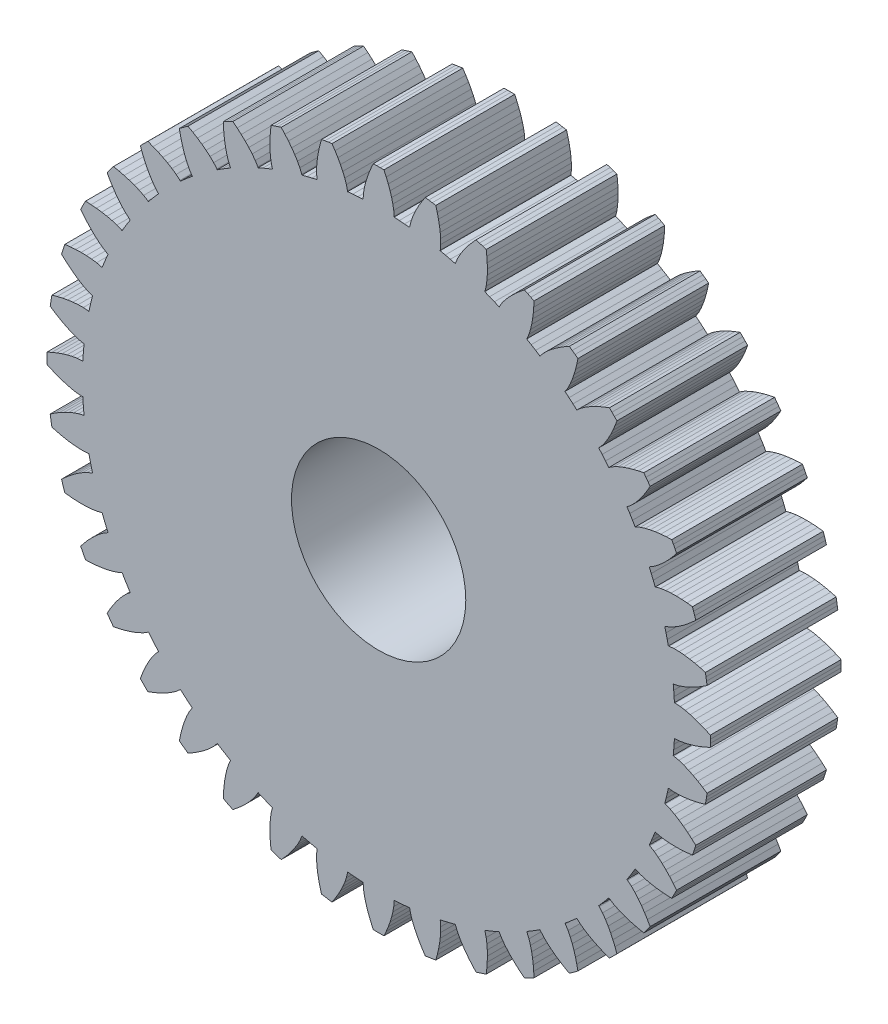
SolidWorks part; units mm, degrees
ref_plane "Спереди" through (0, 0, 0) normal (0, 0, 1) x (1, 0, 0)
ref_plane "Сверху" through (0, 0, 0) normal (0, 1, 0) x (1, 0, 0)
ref_plane "Справа" through (0, 0, 0) normal (1, 0, 0) x (0, 0, -1)
sketch "Эскиз1" plane through (0, 0, 0) normal (0, 0, 1) x (1, 0, 0)
  line L0 (27.1506, -1.416) -> (27.2141, -1.4193)
  line L1 (27.2141, -1.4193) -> (27.6733, -1.3869)
  line L2 (27.6733, -1.3869) -> (28.1347, -1.3064)
  line L3 (28.1347, -1.3064) -> (28.5972, -1.1932)
  line L4 (28.5972, -1.1932) -> (29.06, -1.0524)
  line L5 (29.06, -1.0524) -> (29.5227, -0.8869)
  line L6 (29.5227, -0.8869) -> (29.9849, -0.6985)
  line L7 (29.9849, -0.6985) -> (30.4461, -0.4885)
  line L8 (30.4461, -0.4885) -> (30.4496, -0.1628)
  line L9 (30.4496, -0.1628) -> (30.4496, 0.1628)
  line L10 (30.4496, 0.1628) -> (30.4461, 0.4885)
  line L11 (30.4461, 0.4885) -> (29.9849, 0.6985)
  line L12 (29.9849, 0.6985) -> (29.5227, 0.8869)
  line L13 (29.5227, 0.8869) -> (29.06, 1.0524)
  line L14 (29.06, 1.0524) -> (28.5972, 1.1932)
  line L15 (28.5972, 1.1932) -> (28.1347, 1.3064)
  line L16 (28.1347, 1.3064) -> (27.6733, 1.3869)
  line L17 (27.6733, 1.3869) -> (27.2141, 1.4193)
  line L18 (27.2141, 1.4193) -> (27.1506, 1.416)
  line L19 (27.1506, 1.416) -> (27.1214, 1.8942)
  line L20 (27.1214, 1.8942) -> (27.0838, 2.3718)
  line L21 (27.0838, 2.3718) -> (27.0378, 2.8488)
  line L22 (27.0378, 2.8488) -> (27.1011, 2.8554)
  line L23 (27.1011, 2.8554) -> (27.5496, 2.9593)
  line L24 (27.5496, 2.9593) -> (27.9927, 3.1109)
  line L25 (27.9927, 3.1109) -> (28.4317, 3.2951)
  line L26 (28.4317, 3.2951) -> (28.8668, 3.5065)
  line L27 (28.8668, 3.5065) -> (29.298, 3.7424)
  line L28 (29.298, 3.7424) -> (29.725, 4.0008)
  line L29 (29.725, 4.0008) -> (30.1477, 4.2804)
  line L30 (30.1477, 4.2804) -> (30.1002, 4.6025)
  line L31 (30.1002, 4.6025) -> (30.0492, 4.9242)
  line L32 (30.0492, 4.9242) -> (29.9948, 5.2453)
  line L33 (29.9948, 5.2453) -> (29.5064, 5.3805)
  line L34 (29.5064, 5.3805) -> (29.0205, 5.4943)
  line L35 (29.0205, 5.4943) -> (28.5376, 5.5854)
  line L36 (28.5376, 5.5854) -> (28.0584, 5.6521)
  line L37 (28.0584, 5.6521) -> (27.584, 5.6915)
  line L38 (27.584, 5.6915) -> (27.1157, 5.6988)
  line L39 (27.1157, 5.6988) -> (26.657, 5.659)
  line L40 (26.657, 5.659) -> (26.5948, 5.6458)
  line L41 (26.5948, 5.6458) -> (26.4912, 6.1136)
  line L42 (26.4912, 6.1136) -> (26.3794, 6.5795)
  line L43 (26.3794, 6.5795) -> (26.2593, 7.0433)
  line L44 (26.2593, 7.0433) -> (26.3207, 7.0598)
  line L45 (26.3207, 7.0598) -> (26.7475, 7.2326)
  line L46 (26.7475, 7.2326) -> (27.1614, 7.4517)
  line L47 (27.1614, 7.4517) -> (27.5662, 7.7022)
  line L48 (27.5662, 7.7022) -> (27.9629, 7.9791)
  line L49 (27.9629, 7.9791) -> (28.3518, 8.2795)
  line L50 (28.3518, 8.2795) -> (28.7332, 8.6015)
  line L51 (28.7332, 8.6015) -> (29.1069, 8.9438)
  line L52 (29.1069, 8.9438) -> (29.0096, 9.2546)
  line L53 (29.0096, 9.2546) -> (28.9089, 9.5643)
  line L54 (28.9089, 9.5643) -> (28.805, 9.8729)
  line L55 (28.805, 9.8729) -> (28.3015, 9.9301)
  line L56 (28.3015, 9.9301) -> (27.8037, 9.9665)
  line L57 (27.8037, 9.9665) -> (27.3125, 9.9809)
  line L58 (27.3125, 9.9809) -> (26.8288, 9.9718)
  line L59 (26.8288, 9.9718) -> (26.354, 9.9366)
  line L60 (26.354, 9.9366) -> (25.8904, 9.8705)
  line L61 (25.8904, 9.8705) -> (25.4436, 9.7594)
  line L62 (25.4436, 9.7594) -> (25.3842, 9.7367)
  line L63 (25.3842, 9.7367) -> (25.2087, 10.1825)
  line L64 (25.2087, 10.1825) -> (25.0253, 10.6251)
  line L65 (25.0253, 10.6251) -> (24.8342, 11.0645)
  line L66 (24.8342, 11.0645) -> (24.8923, 11.0904)
  line L67 (24.8923, 11.0904) -> (25.2867, 11.3277)
  line L68 (25.2867, 11.3277) -> (25.6613, 11.6089)
  line L69 (25.6613, 11.6089) -> (26.022, 11.9197)
  line L70 (26.022, 11.9197) -> (26.3704, 12.2553)
  line L71 (26.3704, 12.2553) -> (26.7076, 12.6128)
  line L72 (26.7076, 12.6128) -> (27.0338, 12.9905)
  line L73 (27.0338, 12.9905) -> (27.3494, 13.387)
  line L74 (27.3494, 13.387) -> (27.2047, 13.6787)
  line L75 (27.2047, 13.6787) -> (27.0568, 13.9689)
  line L76 (27.0568, 13.9689) -> (26.9059, 14.2575)
  line L77 (26.9059, 14.2575) -> (26.3996, 14.2352)
  line L78 (26.3996, 14.2352) -> (25.9023, 14.1932)
  line L79 (25.9023, 14.1932) -> (25.4149, 14.1307)
  line L80 (25.4149, 14.1307) -> (24.9386, 14.046)
  line L81 (24.9386, 14.046) -> (24.4752, 13.9369)
  line L82 (24.4752, 13.9369) -> (24.0275, 13.7991)
  line L83 (24.0275, 13.7991) -> (23.6036, 13.6195)
  line L84 (23.6036, 13.6195) -> (23.5485, 13.5878)
  line L85 (23.5485, 13.5878) -> (23.3054, 14.0006)
  line L86 (23.3054, 14.0006) -> (23.0551, 14.4091)
  line L87 (23.0551, 14.4091) -> (22.7976, 14.8132)
  line L88 (22.7976, 14.8132) -> (22.8509, 14.8478)
  line L89 (22.8509, 14.8478) -> (23.2034, 15.144)
  line L90 (23.2034, 15.144) -> (23.5294, 15.4803)
  line L91 (23.5294, 15.4803) -> (23.8369, 15.8437)
  line L92 (23.8369, 15.8437) -> (24.1286, 16.2296)
  line L93 (24.1286, 16.2296) -> (24.4057, 16.6355)
  line L94 (24.4057, 16.6355) -> (24.6688, 17.0596)
  line L95 (24.6688, 17.0596) -> (24.9185, 17.5006)
  line L96 (24.9185, 17.5006) -> (24.7299, 17.7661)
  line L97 (24.7299, 17.7661) -> (24.5385, 18.0295)
  line L98 (24.5385, 18.0295) -> (24.3443, 18.2909)
  line L99 (24.3443, 18.2909) -> (23.8477, 18.1897)
  line L100 (23.8477, 18.1897) -> (23.3631, 18.0705)
  line L101 (23.3631, 18.0705) -> (22.8914, 17.9324)
  line L102 (22.8914, 17.9324) -> (22.4343, 17.7743)
  line L103 (22.4343, 17.7743) -> (21.9936, 17.5941)
  line L104 (21.9936, 17.5941) -> (21.573, 17.388)
  line L105 (21.573, 17.388) -> (21.1824, 17.1443)
  line L106 (21.1824, 17.1443) -> (21.133, 17.1043)
  line L107 (21.133, 17.1043) -> (20.8283, 17.474)
  line L108 (20.8283, 17.474) -> (20.5172, 17.8383)
  line L109 (20.5172, 17.8383) -> (20.1996, 18.1971)
  line L110 (20.1996, 18.1971) -> (20.2469, 18.2397)
  line L111 (20.2469, 18.2397) -> (20.5487, 18.5874)
  line L112 (20.5487, 18.5874) -> (20.818, 18.9705)
  line L113 (20.818, 18.9705) -> (21.065, 19.3775)
  line L114 (21.065, 19.3775) -> (21.2927, 19.8044)
  line L115 (21.2927, 19.8044) -> (21.5028, 20.2486)
  line L116 (21.5028, 20.2486) -> (21.6964, 20.7086)
  line L117 (21.6964, 20.7086) -> (21.874, 21.1832)
  line L118 (21.874, 21.1832) -> (21.6462, 21.416)
  line L119 (21.6462, 21.416) -> (21.416, 21.6462)
  line L120 (21.416, 21.6462) -> (21.1832, 21.874)
  line L121 (21.1832, 21.874) -> (20.7086, 21.6964)
  line L122 (20.7086, 21.6964) -> (20.2486, 21.5028)
  line L123 (20.2486, 21.5028) -> (19.8044, 21.2927)
  line L124 (19.8044, 21.2927) -> (19.3775, 21.065)
  line L125 (19.3775, 21.065) -> (18.9705, 20.818)
  line L126 (18.9705, 20.818) -> (18.5874, 20.5487)
  line L127 (18.5874, 20.5487) -> (18.2397, 20.2469)
  line L128 (18.2397, 20.2469) -> (18.1971, 20.1996)
  line L129 (18.1971, 20.1996) -> (17.8383, 20.5172)
  line L130 (17.8383, 20.5172) -> (17.474, 20.8283)
  line L131 (17.474, 20.8283) -> (17.1043, 21.133)
  line L132 (17.1043, 21.133) -> (17.1443, 21.1824)
  line L133 (17.1443, 21.1824) -> (17.388, 21.573)
  line L134 (17.388, 21.573) -> (17.5941, 21.9936)
  line L135 (17.5941, 21.9936) -> (17.7743, 22.4343)
  line L136 (17.7743, 22.4343) -> (17.9324, 22.8914)
  line L137 (17.9324, 22.8914) -> (18.0705, 23.3631)
  line L138 (18.0705, 23.3631) -> (18.1897, 23.8477)
  line L139 (18.1897, 23.8477) -> (18.2909, 24.3443)
  line L140 (18.2909, 24.3443) -> (18.0295, 24.5385)
  line L141 (18.0295, 24.5385) -> (17.7661, 24.7299)
  line L142 (17.7661, 24.7299) -> (17.5006, 24.9185)
  line L143 (17.5006, 24.9185) -> (17.0596, 24.6688)
  line L144 (17.0596, 24.6688) -> (16.6355, 24.4057)
  line L145 (16.6355, 24.4057) -> (16.2296, 24.1286)
  line L146 (16.2296, 24.1286) -> (15.8437, 23.8369)
  line L147 (15.8437, 23.8369) -> (15.4803, 23.5294)
  line L148 (15.4803, 23.5294) -> (15.144, 23.2034)
  line L149 (15.144, 23.2034) -> (14.8478, 22.8509)
  line L150 (14.8478, 22.8509) -> (14.8132, 22.7976)
  line L151 (14.8132, 22.7976) -> (14.4091, 23.0551)
  line L152 (14.4091, 23.0551) -> (14.0006, 23.3054)
  line L153 (14.0006, 23.3054) -> (13.5878, 23.5485)
  line L154 (13.5878, 23.5485) -> (13.6195, 23.6036)
  line L155 (13.6195, 23.6036) -> (13.7991, 24.0275)
  line L156 (13.7991, 24.0275) -> (13.9369, 24.4752)
  line L157 (13.9369, 24.4752) -> (14.046, 24.9386)
  line L158 (14.046, 24.9386) -> (14.1307, 25.4149)
  line L159 (14.1307, 25.4149) -> (14.1932, 25.9023)
  line L160 (14.1932, 25.9023) -> (14.2352, 26.3996)
  line L161 (14.2352, 26.3996) -> (14.2575, 26.9059)
  line L162 (14.2575, 26.9059) -> (13.9689, 27.0568)
  line L163 (13.9689, 27.0568) -> (13.6787, 27.2047)
  line L164 (13.6787, 27.2047) -> (13.387, 27.3494)
  line L165 (13.387, 27.3494) -> (12.9905, 27.0338)
  line L166 (12.9905, 27.0338) -> (12.6128, 26.7076)
  line L167 (12.6128, 26.7076) -> (12.2553, 26.3704)
  line L168 (12.2553, 26.3704) -> (11.9197, 26.022)
  line L169 (11.9197, 26.022) -> (11.6089, 25.6613)
  line L170 (11.6089, 25.6613) -> (11.3277, 25.2867)
  line L171 (11.3277, 25.2867) -> (11.0904, 24.8923)
  line L172 (11.0904, 24.8923) -> (11.0645, 24.8342)
  line L173 (11.0645, 24.8342) -> (10.6251, 25.0253)
  line L174 (10.6251, 25.0253) -> (10.1825, 25.2087)
  line L175 (10.1825, 25.2087) -> (9.7367, 25.3842)
  line L176 (9.7367, 25.3842) -> (9.7594, 25.4436)
  line L177 (9.7594, 25.4436) -> (9.8705, 25.8904)
  line L178 (9.8705, 25.8904) -> (9.9366, 26.354)
  line L179 (9.9366, 26.354) -> (9.9718, 26.8288)
  line L180 (9.9718, 26.8288) -> (9.9809, 27.3125)
  line L181 (9.9809, 27.3125) -> (9.9665, 27.8037)
  line L182 (9.9665, 27.8037) -> (9.9301, 28.3015)
  line L183 (9.9301, 28.3015) -> (9.8729, 28.805)
  line L184 (9.8729, 28.805) -> (9.5643, 28.9089)
  line L185 (9.5643, 28.9089) -> (9.2546, 29.0096)
  line L186 (9.2546, 29.0096) -> (8.9438, 29.1069)
  line L187 (8.9438, 29.1069) -> (8.6015, 28.7332)
  line L188 (8.6015, 28.7332) -> (8.2795, 28.3518)
  line L189 (8.2795, 28.3518) -> (7.9791, 27.9629)
  line L190 (7.9791, 27.9629) -> (7.7022, 27.5662)
  line L191 (7.7022, 27.5662) -> (7.4517, 27.1614)
  line L192 (7.4517, 27.1614) -> (7.2326, 26.7475)
  line L193 (7.2326, 26.7475) -> (7.0598, 26.3207)
  line L194 (7.0598, 26.3207) -> (7.0433, 26.2593)
  line L195 (7.0433, 26.2593) -> (6.5795, 26.3794)
  line L196 (6.5795, 26.3794) -> (6.1136, 26.4912)
  line L197 (6.1136, 26.4912) -> (5.6458, 26.5948)
  line L198 (5.6458, 26.5948) -> (5.659, 26.657)
  line L199 (5.659, 26.657) -> (5.6988, 27.1157)
  line L200 (5.6988, 27.1157) -> (5.6915, 27.584)
  line L201 (5.6915, 27.584) -> (5.6521, 28.0584)
  line L202 (5.6521, 28.0584) -> (5.5854, 28.5376)
  line L203 (5.5854, 28.5376) -> (5.4943, 29.0205)
  line L204 (5.4943, 29.0205) -> (5.3805, 29.5064)
  line L205 (5.3805, 29.5064) -> (5.2453, 29.9948)
  line L206 (5.2453, 29.9948) -> (4.9242, 30.0492)
  line L207 (4.9242, 30.0492) -> (4.6025, 30.1002)
  line L208 (4.6025, 30.1002) -> (4.2804, 30.1477)
  line L209 (4.2804, 30.1477) -> (4.0008, 29.725)
  line L210 (4.0008, 29.725) -> (3.7424, 29.298)
  line L211 (3.7424, 29.298) -> (3.5065, 28.8668)
  line L212 (3.5065, 28.8668) -> (3.2951, 28.4317)
  line L213 (3.2951, 28.4317) -> (3.1109, 27.9927)
  line L214 (3.1109, 27.9927) -> (2.9593, 27.5496)
  line L215 (2.9593, 27.5496) -> (2.8554, 27.1011)
  line L216 (2.8554, 27.1011) -> (2.8488, 27.0378)
  line L217 (2.8488, 27.0378) -> (2.3718, 27.0838)
  line L218 (2.3718, 27.0838) -> (1.8942, 27.1214)
  line L219 (1.8942, 27.1214) -> (1.416, 27.1506)
  line L220 (1.416, 27.1506) -> (1.4193, 27.2141)
  line L221 (1.4193, 27.2141) -> (1.3869, 27.6733)
  line L222 (1.3869, 27.6733) -> (1.3064, 28.1347)
  line L223 (1.3064, 28.1347) -> (1.1932, 28.5972)
  line L224 (1.1932, 28.5972) -> (1.0524, 29.06)
  line L225 (1.0524, 29.06) -> (0.8869, 29.5227)
  line L226 (0.8869, 29.5227) -> (0.6985, 29.9849)
  line L227 (0.6985, 29.9849) -> (0.4885, 30.4461)
  line L228 (0.4885, 30.4461) -> (0.1628, 30.4496)
  line L229 (0.1628, 30.4496) -> (-0.1628, 30.4496)
  line L230 (-0.1628, 30.4496) -> (-0.4885, 30.4461)
  line L231 (-0.4885, 30.4461) -> (-0.6985, 29.9849)
  line L232 (-0.6985, 29.9849) -> (-0.8869, 29.5227)
  line L233 (-0.8869, 29.5227) -> (-1.0524, 29.06)
  line L234 (-1.0524, 29.06) -> (-1.1932, 28.5972)
  line L235 (-1.1932, 28.5972) -> (-1.3064, 28.1347)
  line L236 (-1.3064, 28.1347) -> (-1.3869, 27.6733)
  line L237 (-1.3869, 27.6733) -> (-1.4193, 27.2141)
  line L238 (-1.4193, 27.2141) -> (-1.416, 27.1506)
  line L239 (-1.416, 27.1506) -> (-1.8942, 27.1214)
  line L240 (-1.8942, 27.1214) -> (-2.3718, 27.0838)
  line L241 (-2.3718, 27.0838) -> (-2.8488, 27.0378)
  line L242 (-2.8488, 27.0378) -> (-2.8554, 27.1011)
  line L243 (-2.8554, 27.1011) -> (-2.9593, 27.5496)
  line L244 (-2.9593, 27.5496) -> (-3.1109, 27.9927)
  line L245 (-3.1109, 27.9927) -> (-3.2951, 28.4317)
  line L246 (-3.2951, 28.4317) -> (-3.5065, 28.8668)
  line L247 (-3.5065, 28.8668) -> (-3.7424, 29.298)
  line L248 (-3.7424, 29.298) -> (-4.0008, 29.725)
  line L249 (-4.0008, 29.725) -> (-4.2804, 30.1477)
  line L250 (-4.2804, 30.1477) -> (-4.6025, 30.1002)
  line L251 (-4.6025, 30.1002) -> (-4.9242, 30.0492)
  line L252 (-4.9242, 30.0492) -> (-5.2453, 29.9948)
  line L253 (-5.2453, 29.9948) -> (-5.3805, 29.5064)
  line L254 (-5.3805, 29.5064) -> (-5.4943, 29.0205)
  line L255 (-5.4943, 29.0205) -> (-5.5854, 28.5376)
  line L256 (-5.5854, 28.5376) -> (-5.6521, 28.0584)
  line L257 (-5.6521, 28.0584) -> (-5.6915, 27.584)
  line L258 (-5.6915, 27.584) -> (-5.6988, 27.1157)
  line L259 (-5.6988, 27.1157) -> (-5.659, 26.657)
  line L260 (-5.659, 26.657) -> (-5.6458, 26.5948)
  line L261 (-5.6458, 26.5948) -> (-6.1136, 26.4912)
  line L262 (-6.1136, 26.4912) -> (-6.5795, 26.3794)
  line L263 (-6.5795, 26.3794) -> (-7.0433, 26.2593)
  line L264 (-7.0433, 26.2593) -> (-7.0598, 26.3207)
  line L265 (-7.0598, 26.3207) -> (-7.2326, 26.7475)
  line L266 (-7.2326, 26.7475) -> (-7.4517, 27.1614)
  line L267 (-7.4517, 27.1614) -> (-7.7022, 27.5662)
  line L268 (-7.7022, 27.5662) -> (-7.9791, 27.9629)
  line L269 (-7.9791, 27.9629) -> (-8.2795, 28.3518)
  line L270 (-8.2795, 28.3518) -> (-8.6015, 28.7332)
  line L271 (-8.6015, 28.7332) -> (-8.9438, 29.1069)
  line L272 (-8.9438, 29.1069) -> (-9.2546, 29.0096)
  line L273 (-9.2546, 29.0096) -> (-9.5643, 28.9089)
  line L274 (-9.5643, 28.9089) -> (-9.8729, 28.805)
  line L275 (-9.8729, 28.805) -> (-9.9301, 28.3015)
  line L276 (-9.9301, 28.3015) -> (-9.9665, 27.8037)
  line L277 (-9.9665, 27.8037) -> (-9.9809, 27.3125)
  line L278 (-9.9809, 27.3125) -> (-9.9718, 26.8288)
  line L279 (-9.9718, 26.8288) -> (-9.9366, 26.354)
  line L280 (-9.9366, 26.354) -> (-9.8705, 25.8904)
  line L281 (-9.8705, 25.8904) -> (-9.7594, 25.4436)
  line L282 (-9.7594, 25.4436) -> (-9.7367, 25.3842)
  line L283 (-9.7367, 25.3842) -> (-10.1825, 25.2087)
  line L284 (-10.1825, 25.2087) -> (-10.6251, 25.0253)
  line L285 (-10.6251, 25.0253) -> (-11.0645, 24.8342)
  line L286 (-11.0645, 24.8342) -> (-11.0904, 24.8923)
  line L287 (-11.0904, 24.8923) -> (-11.3277, 25.2867)
  line L288 (-11.3277, 25.2867) -> (-11.6089, 25.6613)
  line L289 (-11.6089, 25.6613) -> (-11.9197, 26.022)
  line L290 (-11.9197, 26.022) -> (-12.2553, 26.3704)
  line L291 (-12.2553, 26.3704) -> (-12.6128, 26.7076)
  line L292 (-12.6128, 26.7076) -> (-12.9905, 27.0338)
  line L293 (-12.9905, 27.0338) -> (-13.387, 27.3494)
  line L294 (-13.387, 27.3494) -> (-13.6787, 27.2047)
  line L295 (-13.6787, 27.2047) -> (-13.9689, 27.0568)
  line L296 (-13.9689, 27.0568) -> (-14.2575, 26.9059)
  line L297 (-14.2575, 26.9059) -> (-14.2352, 26.3996)
  line L298 (-14.2352, 26.3996) -> (-14.1932, 25.9023)
  line L299 (-14.1932, 25.9023) -> (-14.1307, 25.4149)
  line L300 (-14.1307, 25.4149) -> (-14.046, 24.9386)
  line L301 (-14.046, 24.9386) -> (-13.9369, 24.4752)
  line L302 (-13.9369, 24.4752) -> (-13.7991, 24.0275)
  line L303 (-13.7991, 24.0275) -> (-13.6195, 23.6036)
  line L304 (-13.6195, 23.6036) -> (-13.5878, 23.5485)
  line L305 (-13.5878, 23.5485) -> (-14.0006, 23.3054)
  line L306 (-14.0006, 23.3054) -> (-14.4091, 23.0551)
  line L307 (-14.4091, 23.0551) -> (-14.8132, 22.7976)
  line L308 (-14.8132, 22.7976) -> (-14.8478, 22.8509)
  line L309 (-14.8478, 22.8509) -> (-15.144, 23.2034)
  line L310 (-15.144, 23.2034) -> (-15.4803, 23.5294)
  line L311 (-15.4803, 23.5294) -> (-15.8437, 23.8369)
  line L312 (-15.8437, 23.8369) -> (-16.2296, 24.1286)
  line L313 (-16.2296, 24.1286) -> (-16.6355, 24.4057)
  line L314 (-16.6355, 24.4057) -> (-17.0596, 24.6688)
  line L315 (-17.0596, 24.6688) -> (-17.5006, 24.9185)
  line L316 (-17.5006, 24.9185) -> (-17.7661, 24.7299)
  line L317 (-17.7661, 24.7299) -> (-18.0295, 24.5385)
  line L318 (-18.0295, 24.5385) -> (-18.2909, 24.3443)
  line L319 (-18.2909, 24.3443) -> (-18.1897, 23.8477)
  line L320 (-18.1897, 23.8477) -> (-18.0705, 23.3631)
  line L321 (-18.0705, 23.3631) -> (-17.9324, 22.8914)
  line L322 (-17.9324, 22.8914) -> (-17.7743, 22.4343)
  line L323 (-17.7743, 22.4343) -> (-17.5941, 21.9936)
  line L324 (-17.5941, 21.9936) -> (-17.388, 21.573)
  line L325 (-17.388, 21.573) -> (-17.1443, 21.1824)
  line L326 (-17.1443, 21.1824) -> (-17.1043, 21.133)
  line L327 (-17.1043, 21.133) -> (-17.474, 20.8283)
  line L328 (-17.474, 20.8283) -> (-17.8383, 20.5172)
  line L329 (-17.8383, 20.5172) -> (-18.1971, 20.1996)
  line L330 (-18.1971, 20.1996) -> (-18.2397, 20.2469)
  line L331 (-18.2397, 20.2469) -> (-18.5874, 20.5487)
  line L332 (-18.5874, 20.5487) -> (-18.9705, 20.818)
  line L333 (-18.9705, 20.818) -> (-19.3775, 21.065)
  line L334 (-19.3775, 21.065) -> (-19.8044, 21.2927)
  line L335 (-19.8044, 21.2927) -> (-20.2486, 21.5028)
  line L336 (-20.2486, 21.5028) -> (-20.7086, 21.6964)
  line L337 (-20.7086, 21.6964) -> (-21.1832, 21.874)
  line L338 (-21.1832, 21.874) -> (-21.416, 21.6462)
  line L339 (-21.416, 21.6462) -> (-21.6462, 21.416)
  line L340 (-21.6462, 21.416) -> (-21.874, 21.1832)
  line L341 (-21.874, 21.1832) -> (-21.6964, 20.7086)
  line L342 (-21.6964, 20.7086) -> (-21.5028, 20.2486)
  line L343 (-21.5028, 20.2486) -> (-21.2927, 19.8044)
  line L344 (-21.2927, 19.8044) -> (-21.065, 19.3775)
  line L345 (-21.065, 19.3775) -> (-20.818, 18.9705)
  line L346 (-20.818, 18.9705) -> (-20.5487, 18.5874)
  line L347 (-20.5487, 18.5874) -> (-20.2469, 18.2397)
  line L348 (-20.2469, 18.2397) -> (-20.1996, 18.1971)
  line L349 (-20.1996, 18.1971) -> (-20.5172, 17.8383)
  line L350 (-20.5172, 17.8383) -> (-20.8283, 17.474)
  line L351 (-20.8283, 17.474) -> (-21.133, 17.1043)
  line L352 (-21.133, 17.1043) -> (-21.1824, 17.1443)
  line L353 (-21.1824, 17.1443) -> (-21.573, 17.388)
  line L354 (-21.573, 17.388) -> (-21.9936, 17.5941)
  line L355 (-21.9936, 17.5941) -> (-22.4343, 17.7743)
  line L356 (-22.4343, 17.7743) -> (-22.8914, 17.9324)
  line L357 (-22.8914, 17.9324) -> (-23.3631, 18.0705)
  line L358 (-23.3631, 18.0705) -> (-23.8477, 18.1897)
  line L359 (-23.8477, 18.1897) -> (-24.3443, 18.2909)
  line L360 (-24.3443, 18.2909) -> (-24.5385, 18.0295)
  line L361 (-24.5385, 18.0295) -> (-24.7299, 17.7661)
  line L362 (-24.7299, 17.7661) -> (-24.9185, 17.5006)
  line L363 (-24.9185, 17.5006) -> (-24.6688, 17.0596)
  line L364 (-24.6688, 17.0596) -> (-24.4057, 16.6355)
  line L365 (-24.4057, 16.6355) -> (-24.1286, 16.2296)
  line L366 (-24.1286, 16.2296) -> (-23.8369, 15.8437)
  line L367 (-23.8369, 15.8437) -> (-23.5294, 15.4803)
  line L368 (-23.5294, 15.4803) -> (-23.2034, 15.144)
  line L369 (-23.2034, 15.144) -> (-22.8509, 14.8478)
  line L370 (-22.8509, 14.8478) -> (-22.7976, 14.8132)
  line L371 (-22.7976, 14.8132) -> (-23.0551, 14.4091)
  line L372 (-23.0551, 14.4091) -> (-23.3054, 14.0006)
  line L373 (-23.3054, 14.0006) -> (-23.5485, 13.5878)
  line L374 (-23.5485, 13.5878) -> (-23.6036, 13.6195)
  line L375 (-23.6036, 13.6195) -> (-24.0275, 13.7991)
  line L376 (-24.0275, 13.7991) -> (-24.4752, 13.9369)
  line L377 (-24.4752, 13.9369) -> (-24.9386, 14.046)
  line L378 (-24.9386, 14.046) -> (-25.4149, 14.1307)
  line L379 (-25.4149, 14.1307) -> (-25.9023, 14.1932)
  line L380 (-25.9023, 14.1932) -> (-26.3996, 14.2352)
  line L381 (-26.3996, 14.2352) -> (-26.9059, 14.2575)
  line L382 (-26.9059, 14.2575) -> (-27.0568, 13.9689)
  line L383 (-27.0568, 13.9689) -> (-27.2047, 13.6787)
  line L384 (-27.2047, 13.6787) -> (-27.3494, 13.387)
  line L385 (-27.3494, 13.387) -> (-27.0338, 12.9905)
  line L386 (-27.0338, 12.9905) -> (-26.7076, 12.6128)
  line L387 (-26.7076, 12.6128) -> (-26.3704, 12.2553)
  line L388 (-26.3704, 12.2553) -> (-26.022, 11.9197)
  line L389 (-26.022, 11.9197) -> (-25.6613, 11.6089)
  line L390 (-25.6613, 11.6089) -> (-25.2867, 11.3277)
  line L391 (-25.2867, 11.3277) -> (-24.8923, 11.0904)
  line L392 (-24.8923, 11.0904) -> (-24.8342, 11.0645)
  line L393 (-24.8342, 11.0645) -> (-25.0253, 10.6251)
  line L394 (-25.0253, 10.6251) -> (-25.2087, 10.1825)
  line L395 (-25.2087, 10.1825) -> (-25.3842, 9.7367)
  line L396 (-25.3842, 9.7367) -> (-25.4436, 9.7594)
  line L397 (-25.4436, 9.7594) -> (-25.8904, 9.8705)
  line L398 (-25.8904, 9.8705) -> (-26.354, 9.9366)
  line L399 (-26.354, 9.9366) -> (-26.8288, 9.9718)
  line L400 (-26.8288, 9.9718) -> (-27.3125, 9.9809)
  line L401 (-27.3125, 9.9809) -> (-27.8037, 9.9665)
  line L402 (-27.8037, 9.9665) -> (-28.3015, 9.9301)
  line L403 (-28.3015, 9.9301) -> (-28.805, 9.8729)
  line L404 (-28.805, 9.8729) -> (-28.9089, 9.5643)
  line L405 (-28.9089, 9.5643) -> (-29.0096, 9.2546)
  line L406 (-29.0096, 9.2546) -> (-29.1069, 8.9438)
  line L407 (-29.1069, 8.9438) -> (-28.7332, 8.6015)
  line L408 (-28.7332, 8.6015) -> (-28.3518, 8.2795)
  line L409 (-28.3518, 8.2795) -> (-27.9629, 7.9791)
  line L410 (-27.9629, 7.9791) -> (-27.5662, 7.7022)
  line L411 (-27.5662, 7.7022) -> (-27.1614, 7.4517)
  line L412 (-27.1614, 7.4517) -> (-26.7475, 7.2326)
  line L413 (-26.7475, 7.2326) -> (-26.3207, 7.0598)
  line L414 (-26.3207, 7.0598) -> (-26.2593, 7.0433)
  line L415 (-26.2593, 7.0433) -> (-26.3794, 6.5795)
  line L416 (-26.3794, 6.5795) -> (-26.4912, 6.1136)
  line L417 (-26.4912, 6.1136) -> (-26.5948, 5.6458)
  line L418 (-26.5948, 5.6458) -> (-26.657, 5.659)
  line L419 (-26.657, 5.659) -> (-27.1157, 5.6988)
  line L420 (-27.1157, 5.6988) -> (-27.584, 5.6915)
  line L421 (-27.584, 5.6915) -> (-28.0584, 5.6521)
  line L422 (-28.0584, 5.6521) -> (-28.5376, 5.5854)
  line L423 (-28.5376, 5.5854) -> (-29.0205, 5.4943)
  line L424 (-29.0205, 5.4943) -> (-29.5064, 5.3805)
  line L425 (-29.5064, 5.3805) -> (-29.9948, 5.2453)
  line L426 (-29.9948, 5.2453) -> (-30.0492, 4.9242)
  line L427 (-30.0492, 4.9242) -> (-30.1002, 4.6025)
  line L428 (-30.1002, 4.6025) -> (-30.1477, 4.2804)
  line L429 (-30.1477, 4.2804) -> (-29.725, 4.0008)
  line L430 (-29.725, 4.0008) -> (-29.298, 3.7424)
  line L431 (-29.298, 3.7424) -> (-28.8668, 3.5065)
  line L432 (-28.8668, 3.5065) -> (-28.4317, 3.2951)
  line L433 (-28.4317, 3.2951) -> (-27.9927, 3.1109)
  line L434 (-27.9927, 3.1109) -> (-27.5496, 2.9593)
  line L435 (-27.5496, 2.9593) -> (-27.1011, 2.8554)
  line L436 (-27.1011, 2.8554) -> (-27.0378, 2.8488)
  line L437 (-27.0378, 2.8488) -> (-27.0838, 2.3718)
  line L438 (-27.0838, 2.3718) -> (-27.1214, 1.8942)
  line L439 (-27.1214, 1.8942) -> (-27.1506, 1.416)
  line L440 (-27.1506, 1.416) -> (-27.2141, 1.4193)
  line L441 (-27.2141, 1.4193) -> (-27.6733, 1.3869)
  line L442 (-27.6733, 1.3869) -> (-28.1347, 1.3064)
  line L443 (-28.1347, 1.3064) -> (-28.5972, 1.1932)
  line L444 (-28.5972, 1.1932) -> (-29.06, 1.0524)
  line L445 (-29.06, 1.0524) -> (-29.5227, 0.8869)
  line L446 (-29.5227, 0.8869) -> (-29.9849, 0.6985)
  line L447 (-29.9849, 0.6985) -> (-30.4461, 0.4885)
  line L448 (-30.4461, 0.4885) -> (-30.4496, 0.1628)
  line L449 (-30.4496, 0.1628) -> (-30.4496, -0.1628)
  line L450 (-30.4496, -0.1628) -> (-30.4461, -0.4885)
  line L451 (-30.4461, -0.4885) -> (-29.9849, -0.6985)
  line L452 (-29.9849, -0.6985) -> (-29.5227, -0.8869)
  line L453 (-29.5227, -0.8869) -> (-29.06, -1.0524)
  line L454 (-29.06, -1.0524) -> (-28.5972, -1.1932)
  line L455 (-28.5972, -1.1932) -> (-28.1347, -1.3064)
  line L456 (-28.1347, -1.3064) -> (-27.6733, -1.3869)
  line L457 (-27.6733, -1.3869) -> (-27.2141, -1.4193)
  line L458 (-27.2141, -1.4193) -> (-27.1506, -1.416)
  line L459 (-27.1506, -1.416) -> (-27.1214, -1.8942)
  line L460 (-27.1214, -1.8942) -> (-27.0838, -2.3718)
  line L461 (-27.0838, -2.3718) -> (-27.0378, -2.8488)
  line L462 (-27.0378, -2.8488) -> (-27.1011, -2.8554)
  line L463 (-27.1011, -2.8554) -> (-27.5496, -2.9593)
  line L464 (-27.5496, -2.9593) -> (-27.9927, -3.1109)
  line L465 (-27.9927, -3.1109) -> (-28.4317, -3.2951)
  line L466 (-28.4317, -3.2951) -> (-28.8668, -3.5065)
  line L467 (-28.8668, -3.5065) -> (-29.298, -3.7424)
  line L468 (-29.298, -3.7424) -> (-29.725, -4.0008)
  line L469 (-29.725, -4.0008) -> (-30.1477, -4.2804)
  line L470 (-30.1477, -4.2804) -> (-30.1002, -4.6025)
  line L471 (-30.1002, -4.6025) -> (-30.0492, -4.9242)
  line L472 (-30.0492, -4.9242) -> (-29.9948, -5.2453)
  line L473 (-29.9948, -5.2453) -> (-29.5064, -5.3805)
  line L474 (-29.5064, -5.3805) -> (-29.0205, -5.4943)
  line L475 (-29.0205, -5.4943) -> (-28.5376, -5.5854)
  line L476 (-28.5376, -5.5854) -> (-28.0584, -5.6521)
  line L477 (-28.0584, -5.6521) -> (-27.584, -5.6915)
  line L478 (-27.584, -5.6915) -> (-27.1157, -5.6988)
  line L479 (-27.1157, -5.6988) -> (-26.657, -5.659)
  line L480 (-26.657, -5.659) -> (-26.5948, -5.6458)
  line L481 (-26.5948, -5.6458) -> (-26.4912, -6.1136)
  line L482 (-26.4912, -6.1136) -> (-26.3794, -6.5795)
  line L483 (-26.3794, -6.5795) -> (-26.2593, -7.0433)
  line L484 (-26.2593, -7.0433) -> (-26.3207, -7.0598)
  line L485 (-26.3207, -7.0598) -> (-26.7475, -7.2326)
  line L486 (-26.7475, -7.2326) -> (-27.1614, -7.4517)
  line L487 (-27.1614, -7.4517) -> (-27.5662, -7.7022)
  line L488 (-27.5662, -7.7022) -> (-27.9629, -7.9791)
  line L489 (-27.9629, -7.9791) -> (-28.3518, -8.2795)
  line L490 (-28.3518, -8.2795) -> (-28.7332, -8.6015)
  line L491 (-28.7332, -8.6015) -> (-29.1069, -8.9438)
  line L492 (-29.1069, -8.9438) -> (-29.0096, -9.2546)
  line L493 (-29.0096, -9.2546) -> (-28.9089, -9.5643)
  line L494 (-28.9089, -9.5643) -> (-28.805, -9.8729)
  line L495 (-28.805, -9.8729) -> (-28.3015, -9.9301)
  line L496 (-28.3015, -9.9301) -> (-27.8037, -9.9665)
  line L497 (-27.8037, -9.9665) -> (-27.3125, -9.9809)
  line L498 (-27.3125, -9.9809) -> (-26.8288, -9.9718)
  line L499 (-26.8288, -9.9718) -> (-26.354, -9.9366)
  line L500 (-26.354, -9.9366) -> (-25.8904, -9.8705)
  line L501 (-25.8904, -9.8705) -> (-25.4436, -9.7594)
  line L502 (-25.4436, -9.7594) -> (-25.3842, -9.7367)
  line L503 (-25.3842, -9.7367) -> (-25.2087, -10.1825)
  line L504 (-25.2087, -10.1825) -> (-25.0253, -10.6251)
  line L505 (-25.0253, -10.6251) -> (-24.8342, -11.0645)
  line L506 (-24.8342, -11.0645) -> (-24.8923, -11.0904)
  line L507 (-24.8923, -11.0904) -> (-25.2867, -11.3277)
  line L508 (-25.2867, -11.3277) -> (-25.6613, -11.6089)
  line L509 (-25.6613, -11.6089) -> (-26.022, -11.9197)
  line L510 (-26.022, -11.9197) -> (-26.3704, -12.2553)
  line L511 (-26.3704, -12.2553) -> (-26.7076, -12.6128)
  line L512 (-26.7076, -12.6128) -> (-27.0338, -12.9905)
  line L513 (-27.0338, -12.9905) -> (-27.3494, -13.387)
  line L514 (-27.3494, -13.387) -> (-27.2047, -13.6787)
  line L515 (-27.2047, -13.6787) -> (-27.0568, -13.9689)
  line L516 (-27.0568, -13.9689) -> (-26.9059, -14.2575)
  line L517 (-26.9059, -14.2575) -> (-26.3996, -14.2352)
  line L518 (-26.3996, -14.2352) -> (-25.9023, -14.1932)
  line L519 (-25.9023, -14.1932) -> (-25.4149, -14.1307)
  line L520 (-25.4149, -14.1307) -> (-24.9386, -14.046)
  line L521 (-24.9386, -14.046) -> (-24.4752, -13.9369)
  line L522 (-24.4752, -13.9369) -> (-24.0275, -13.7991)
  line L523 (-24.0275, -13.7991) -> (-23.6036, -13.6195)
  line L524 (-23.6036, -13.6195) -> (-23.5485, -13.5878)
  line L525 (-23.5485, -13.5878) -> (-23.3054, -14.0006)
  line L526 (-23.3054, -14.0006) -> (-23.0551, -14.4091)
  line L527 (-23.0551, -14.4091) -> (-22.7976, -14.8132)
  line L528 (-22.7976, -14.8132) -> (-22.8509, -14.8478)
  line L529 (-22.8509, -14.8478) -> (-23.2034, -15.144)
  line L530 (-23.2034, -15.144) -> (-23.5294, -15.4803)
  line L531 (-23.5294, -15.4803) -> (-23.8369, -15.8437)
  line L532 (-23.8369, -15.8437) -> (-24.1286, -16.2296)
  line L533 (-24.1286, -16.2296) -> (-24.4057, -16.6355)
  line L534 (-24.4057, -16.6355) -> (-24.6688, -17.0596)
  line L535 (-24.6688, -17.0596) -> (-24.9185, -17.5006)
  line L536 (-24.9185, -17.5006) -> (-24.7299, -17.7661)
  line L537 (-24.7299, -17.7661) -> (-24.5385, -18.0295)
  line L538 (-24.5385, -18.0295) -> (-24.3443, -18.2909)
  line L539 (-24.3443, -18.2909) -> (-23.8477, -18.1897)
  line L540 (-23.8477, -18.1897) -> (-23.3631, -18.0705)
  line L541 (-23.3631, -18.0705) -> (-22.8914, -17.9324)
  line L542 (-22.8914, -17.9324) -> (-22.4343, -17.7743)
  line L543 (-22.4343, -17.7743) -> (-21.9936, -17.5941)
  line L544 (-21.9936, -17.5941) -> (-21.573, -17.388)
  line L545 (-21.573, -17.388) -> (-21.1824, -17.1443)
  line L546 (-21.1824, -17.1443) -> (-21.133, -17.1043)
  line L547 (-21.133, -17.1043) -> (-20.8283, -17.474)
  line L548 (-20.8283, -17.474) -> (-20.5172, -17.8383)
  line L549 (-20.5172, -17.8383) -> (-20.1996, -18.1971)
  line L550 (-20.1996, -18.1971) -> (-20.2469, -18.2397)
  line L551 (-20.2469, -18.2397) -> (-20.5487, -18.5874)
  line L552 (-20.5487, -18.5874) -> (-20.818, -18.9705)
  line L553 (-20.818, -18.9705) -> (-21.065, -19.3775)
  line L554 (-21.065, -19.3775) -> (-21.2927, -19.8044)
  line L555 (-21.2927, -19.8044) -> (-21.5028, -20.2486)
  line L556 (-21.5028, -20.2486) -> (-21.6964, -20.7086)
  line L557 (-21.6964, -20.7086) -> (-21.874, -21.1832)
  line L558 (-21.874, -21.1832) -> (-21.6462, -21.416)
  line L559 (-21.6462, -21.416) -> (-21.416, -21.6462)
  line L560 (-21.416, -21.6462) -> (-21.1832, -21.874)
  line L561 (-21.1832, -21.874) -> (-20.7086, -21.6964)
  line L562 (-20.7086, -21.6964) -> (-20.2486, -21.5028)
  line L563 (-20.2486, -21.5028) -> (-19.8044, -21.2927)
  line L564 (-19.8044, -21.2927) -> (-19.3775, -21.065)
  line L565 (-19.3775, -21.065) -> (-18.9705, -20.818)
  line L566 (-18.9705, -20.818) -> (-18.5874, -20.5487)
  line L567 (-18.5874, -20.5487) -> (-18.2397, -20.2469)
  line L568 (-18.2397, -20.2469) -> (-18.1971, -20.1996)
  line L569 (-18.1971, -20.1996) -> (-17.8383, -20.5172)
  line L570 (-17.8383, -20.5172) -> (-17.474, -20.8283)
  line L571 (-17.474, -20.8283) -> (-17.1043, -21.133)
  line L572 (-17.1043, -21.133) -> (-17.1443, -21.1824)
  line L573 (-17.1443, -21.1824) -> (-17.388, -21.573)
  line L574 (-17.388, -21.573) -> (-17.5941, -21.9936)
  line L575 (-17.5941, -21.9936) -> (-17.7743, -22.4343)
  line L576 (-17.7743, -22.4343) -> (-17.9324, -22.8914)
  line L577 (-17.9324, -22.8914) -> (-18.0705, -23.3631)
  line L578 (-18.0705, -23.3631) -> (-18.1897, -23.8477)
  line L579 (-18.1897, -23.8477) -> (-18.2909, -24.3443)
  line L580 (-18.2909, -24.3443) -> (-18.0295, -24.5385)
  line L581 (-18.0295, -24.5385) -> (-17.7661, -24.7299)
  line L582 (-17.7661, -24.7299) -> (-17.5006, -24.9185)
  line L583 (-17.5006, -24.9185) -> (-17.0596, -24.6688)
  line L584 (-17.0596, -24.6688) -> (-16.6355, -24.4057)
  line L585 (-16.6355, -24.4057) -> (-16.2296, -24.1286)
  line L586 (-16.2296, -24.1286) -> (-15.8437, -23.8369)
  line L587 (-15.8437, -23.8369) -> (-15.4803, -23.5294)
  line L588 (-15.4803, -23.5294) -> (-15.144, -23.2034)
  line L589 (-15.144, -23.2034) -> (-14.8478, -22.8509)
  line L590 (-14.8478, -22.8509) -> (-14.8132, -22.7976)
  line L591 (-14.8132, -22.7976) -> (-14.4091, -23.0551)
  line L592 (-14.4091, -23.0551) -> (-14.0006, -23.3054)
  line L593 (-14.0006, -23.3054) -> (-13.5878, -23.5485)
  line L594 (-13.5878, -23.5485) -> (-13.6195, -23.6036)
  line L595 (-13.6195, -23.6036) -> (-13.7991, -24.0275)
  line L596 (-13.7991, -24.0275) -> (-13.9369, -24.4752)
  line L597 (-13.9369, -24.4752) -> (-14.046, -24.9386)
  line L598 (-14.046, -24.9386) -> (-14.1307, -25.4149)
  line L599 (-14.1307, -25.4149) -> (-14.1932, -25.9023)
  line L600 (-14.1932, -25.9023) -> (-14.2352, -26.3996)
  line L601 (-14.2352, -26.3996) -> (-14.2575, -26.9059)
  line L602 (-14.2575, -26.9059) -> (-13.9689, -27.0568)
  line L603 (-13.9689, -27.0568) -> (-13.6787, -27.2047)
  line L604 (-13.6787, -27.2047) -> (-13.387, -27.3494)
  line L605 (-13.387, -27.3494) -> (-12.9905, -27.0338)
  line L606 (-12.9905, -27.0338) -> (-12.6128, -26.7076)
  line L607 (-12.6128, -26.7076) -> (-12.2553, -26.3704)
  line L608 (-12.2553, -26.3704) -> (-11.9197, -26.022)
  line L609 (-11.9197, -26.022) -> (-11.6089, -25.6613)
  line L610 (-11.6089, -25.6613) -> (-11.3277, -25.2867)
  line L611 (-11.3277, -25.2867) -> (-11.0904, -24.8923)
  line L612 (-11.0904, -24.8923) -> (-11.0645, -24.8342)
  line L613 (-11.0645, -24.8342) -> (-10.6251, -25.0253)
  line L614 (-10.6251, -25.0253) -> (-10.1825, -25.2087)
  line L615 (-10.1825, -25.2087) -> (-9.7367, -25.3842)
  line L616 (-9.7367, -25.3842) -> (-9.7594, -25.4436)
  line L617 (-9.7594, -25.4436) -> (-9.8705, -25.8904)
  line L618 (-9.8705, -25.8904) -> (-9.9366, -26.354)
  line L619 (-9.9366, -26.354) -> (-9.9718, -26.8288)
  line L620 (-9.9718, -26.8288) -> (-9.9809, -27.3125)
  line L621 (-9.9809, -27.3125) -> (-9.9665, -27.8037)
  line L622 (-9.9665, -27.8037) -> (-9.9301, -28.3015)
  line L623 (-9.9301, -28.3015) -> (-9.8729, -28.805)
  line L624 (-9.8729, -28.805) -> (-9.5643, -28.9089)
  line L625 (-9.5643, -28.9089) -> (-9.2546, -29.0096)
  line L626 (-9.2546, -29.0096) -> (-8.9438, -29.1069)
  line L627 (-8.9438, -29.1069) -> (-8.6015, -28.7332)
  line L628 (-8.6015, -28.7332) -> (-8.2795, -28.3518)
  line L629 (-8.2795, -28.3518) -> (-7.9791, -27.9629)
  line L630 (-7.9791, -27.9629) -> (-7.7022, -27.5662)
  line L631 (-7.7022, -27.5662) -> (-7.4517, -27.1614)
  line L632 (-7.4517, -27.1614) -> (-7.2326, -26.7475)
  line L633 (-7.2326, -26.7475) -> (-7.0598, -26.3207)
  line L634 (-7.0598, -26.3207) -> (-7.0433, -26.2593)
  line L635 (-7.0433, -26.2593) -> (-6.5795, -26.3794)
  line L636 (-6.5795, -26.3794) -> (-6.1136, -26.4912)
  line L637 (-6.1136, -26.4912) -> (-5.6458, -26.5948)
  line L638 (-5.6458, -26.5948) -> (-5.659, -26.657)
  line L639 (-5.659, -26.657) -> (-5.6988, -27.1157)
  line L640 (-5.6988, -27.1157) -> (-5.6915, -27.584)
  line L641 (-5.6915, -27.584) -> (-5.6521, -28.0584)
  line L642 (-5.6521, -28.0584) -> (-5.5854, -28.5376)
  line L643 (-5.5854, -28.5376) -> (-5.4943, -29.0205)
  line L644 (-5.4943, -29.0205) -> (-5.3805, -29.5064)
  line L645 (-5.3805, -29.5064) -> (-5.2453, -29.9948)
  line L646 (-5.2453, -29.9948) -> (-4.9242, -30.0492)
  line L647 (-4.9242, -30.0492) -> (-4.6025, -30.1002)
  line L648 (-4.6025, -30.1002) -> (-4.2804, -30.1477)
  line L649 (-4.2804, -30.1477) -> (-4.0008, -29.725)
  line L650 (-4.0008, -29.725) -> (-3.7424, -29.298)
  line L651 (-3.7424, -29.298) -> (-3.5065, -28.8668)
  line L652 (-3.5065, -28.8668) -> (-3.2951, -28.4317)
  line L653 (-3.2951, -28.4317) -> (-3.1109, -27.9927)
  line L654 (-3.1109, -27.9927) -> (-2.9593, -27.5496)
  line L655 (-2.9593, -27.5496) -> (-2.8554, -27.1011)
  line L656 (-2.8554, -27.1011) -> (-2.8488, -27.0378)
  line L657 (-2.8488, -27.0378) -> (-2.3718, -27.0838)
  line L658 (-2.3718, -27.0838) -> (-1.8942, -27.1214)
  line L659 (-1.8942, -27.1214) -> (-1.416, -27.1506)
  line L660 (-1.416, -27.1506) -> (-1.4193, -27.2141)
  line L661 (-1.4193, -27.2141) -> (-1.3869, -27.6733)
  line L662 (-1.3869, -27.6733) -> (-1.3064, -28.1347)
  line L663 (-1.3064, -28.1347) -> (-1.1932, -28.5972)
  line L664 (-1.1932, -28.5972) -> (-1.0524, -29.06)
  line L665 (-1.0524, -29.06) -> (-0.8869, -29.5227)
  line L666 (-0.8869, -29.5227) -> (-0.6985, -29.9849)
  line L667 (-0.6985, -29.9849) -> (-0.4885, -30.4461)
  line L668 (-0.4885, -30.4461) -> (-0.1628, -30.4496)
  line L669 (-0.1628, -30.4496) -> (0.1628, -30.4496)
  line L670 (0.1628, -30.4496) -> (0.4885, -30.4461)
  line L671 (0.4885, -30.4461) -> (0.6985, -29.9849)
  line L672 (0.6985, -29.9849) -> (0.8869, -29.5227)
  line L673 (0.8869, -29.5227) -> (1.0524, -29.06)
  line L674 (1.0524, -29.06) -> (1.1932, -28.5972)
  line L675 (1.1932, -28.5972) -> (1.3064, -28.1347)
  line L676 (1.3064, -28.1347) -> (1.3869, -27.6733)
  line L677 (1.3869, -27.6733) -> (1.4193, -27.2141)
  line L678 (1.4193, -27.2141) -> (1.416, -27.1506)
  line L679 (1.416, -27.1506) -> (1.8942, -27.1214)
  line L680 (1.8942, -27.1214) -> (2.3718, -27.0838)
  line L681 (2.3718, -27.0838) -> (2.8488, -27.0378)
  line L682 (2.8488, -27.0378) -> (2.8554, -27.1011)
  line L683 (2.8554, -27.1011) -> (2.9593, -27.5496)
  line L684 (2.9593, -27.5496) -> (3.1109, -27.9927)
  line L685 (3.1109, -27.9927) -> (3.2951, -28.4317)
  line L686 (3.2951, -28.4317) -> (3.5065, -28.8668)
  line L687 (3.5065, -28.8668) -> (3.7424, -29.298)
  line L688 (3.7424, -29.298) -> (4.0008, -29.725)
  line L689 (4.0008, -29.725) -> (4.2804, -30.1477)
  line L690 (4.2804, -30.1477) -> (4.6025, -30.1002)
  line L691 (4.6025, -30.1002) -> (4.9242, -30.0492)
  line L692 (4.9242, -30.0492) -> (5.2453, -29.9948)
  line L693 (5.2453, -29.9948) -> (5.3805, -29.5064)
  line L694 (5.3805, -29.5064) -> (5.4943, -29.0205)
  line L695 (5.4943, -29.0205) -> (5.5854, -28.5376)
  line L696 (5.5854, -28.5376) -> (5.6521, -28.0584)
  line L697 (5.6521, -28.0584) -> (5.6915, -27.584)
  line L698 (5.6915, -27.584) -> (5.6988, -27.1157)
  line L699 (5.6988, -27.1157) -> (5.659, -26.657)
  line L700 (5.659, -26.657) -> (5.6458, -26.5948)
  line L701 (5.6458, -26.5948) -> (6.1136, -26.4912)
  line L702 (6.1136, -26.4912) -> (6.5795, -26.3794)
  line L703 (6.5795, -26.3794) -> (7.0433, -26.2593)
  line L704 (7.0433, -26.2593) -> (7.0598, -26.3207)
  line L705 (7.0598, -26.3207) -> (7.2326, -26.7475)
  line L706 (7.2326, -26.7475) -> (7.4517, -27.1614)
  line L707 (7.4517, -27.1614) -> (7.7022, -27.5662)
  line L708 (7.7022, -27.5662) -> (7.9791, -27.9629)
  line L709 (7.9791, -27.9629) -> (8.2795, -28.3518)
  line L710 (8.2795, -28.3518) -> (8.6015, -28.7332)
  line L711 (8.6015, -28.7332) -> (8.9438, -29.1069)
  line L712 (8.9438, -29.1069) -> (9.2546, -29.0096)
  line L713 (9.2546, -29.0096) -> (9.5643, -28.9089)
  line L714 (9.5643, -28.9089) -> (9.8729, -28.805)
  line L715 (9.8729, -28.805) -> (9.9301, -28.3015)
  line L716 (9.9301, -28.3015) -> (9.9665, -27.8037)
  line L717 (9.9665, -27.8037) -> (9.9809, -27.3125)
  line L718 (9.9809, -27.3125) -> (9.9718, -26.8288)
  line L719 (9.9718, -26.8288) -> (9.9366, -26.354)
  line L720 (9.9366, -26.354) -> (9.8705, -25.8904)
  line L721 (9.8705, -25.8904) -> (9.7594, -25.4436)
  line L722 (9.7594, -25.4436) -> (9.7367, -25.3842)
  line L723 (9.7367, -25.3842) -> (10.1825, -25.2087)
  line L724 (10.1825, -25.2087) -> (10.6251, -25.0253)
  line L725 (10.6251, -25.0253) -> (11.0645, -24.8342)
  line L726 (11.0645, -24.8342) -> (11.0904, -24.8923)
  line L727 (11.0904, -24.8923) -> (11.3277, -25.2867)
  line L728 (11.3277, -25.2867) -> (11.6089, -25.6613)
  line L729 (11.6089, -25.6613) -> (11.9197, -26.022)
  line L730 (11.9197, -26.022) -> (12.2553, -26.3704)
  line L731 (12.2553, -26.3704) -> (12.6128, -26.7076)
  line L732 (12.6128, -26.7076) -> (12.9905, -27.0338)
  line L733 (12.9905, -27.0338) -> (13.387, -27.3494)
  line L734 (13.387, -27.3494) -> (13.6787, -27.2047)
  line L735 (13.6787, -27.2047) -> (13.9689, -27.0568)
  line L736 (13.9689, -27.0568) -> (14.2575, -26.9059)
  line L737 (14.2575, -26.9059) -> (14.2352, -26.3996)
  line L738 (14.2352, -26.3996) -> (14.1932, -25.9023)
  line L739 (14.1932, -25.9023) -> (14.1307, -25.4149)
  line L740 (14.1307, -25.4149) -> (14.046, -24.9386)
  line L741 (14.046, -24.9386) -> (13.9369, -24.4752)
  line L742 (13.9369, -24.4752) -> (13.7991, -24.0275)
  line L743 (13.7991, -24.0275) -> (13.6195, -23.6036)
  line L744 (13.6195, -23.6036) -> (13.5878, -23.5485)
  line L745 (13.5878, -23.5485) -> (14.0006, -23.3054)
  line L746 (14.0006, -23.3054) -> (14.4091, -23.0551)
  line L747 (14.4091, -23.0551) -> (14.8132, -22.7976)
  line L748 (14.8132, -22.7976) -> (14.8478, -22.8509)
  line L749 (14.8478, -22.8509) -> (15.144, -23.2034)
  line L750 (15.144, -23.2034) -> (15.4803, -23.5294)
  line L751 (15.4803, -23.5294) -> (15.8437, -23.8369)
  line L752 (15.8437, -23.8369) -> (16.2296, -24.1286)
  line L753 (16.2296, -24.1286) -> (16.6355, -24.4057)
  line L754 (16.6355, -24.4057) -> (17.0596, -24.6688)
  line L755 (17.0596, -24.6688) -> (17.5006, -24.9185)
  line L756 (17.5006, -24.9185) -> (17.7661, -24.7299)
  line L757 (17.7661, -24.7299) -> (18.0295, -24.5385)
  line L758 (18.0295, -24.5385) -> (18.2909, -24.3443)
  line L759 (18.2909, -24.3443) -> (18.1897, -23.8477)
  line L760 (18.1897, -23.8477) -> (18.0705, -23.3631)
  line L761 (18.0705, -23.3631) -> (17.9324, -22.8914)
  line L762 (17.9324, -22.8914) -> (17.7743, -22.4343)
  line L763 (17.7743, -22.4343) -> (17.5941, -21.9936)
  line L764 (17.5941, -21.9936) -> (17.388, -21.573)
  line L765 (17.388, -21.573) -> (17.1443, -21.1824)
  line L766 (17.1443, -21.1824) -> (17.1043, -21.133)
  line L767 (17.1043, -21.133) -> (17.474, -20.8283)
  line L768 (17.474, -20.8283) -> (17.8383, -20.5172)
  line L769 (17.8383, -20.5172) -> (18.1971, -20.1996)
  line L770 (18.1971, -20.1996) -> (18.2397, -20.2469)
  line L771 (18.2397, -20.2469) -> (18.5874, -20.5487)
  line L772 (18.5874, -20.5487) -> (18.9705, -20.818)
  line L773 (18.9705, -20.818) -> (19.3775, -21.065)
  line L774 (19.3775, -21.065) -> (19.8044, -21.2927)
  line L775 (19.8044, -21.2927) -> (20.2486, -21.5028)
  line L776 (20.2486, -21.5028) -> (20.7086, -21.6964)
  line L777 (20.7086, -21.6964) -> (21.1832, -21.874)
  line L778 (21.1832, -21.874) -> (21.416, -21.6462)
  line L779 (21.416, -21.6462) -> (21.6462, -21.416)
  line L780 (21.6462, -21.416) -> (21.874, -21.1832)
  line L781 (21.874, -21.1832) -> (21.6964, -20.7086)
  line L782 (21.6964, -20.7086) -> (21.5028, -20.2486)
  line L783 (21.5028, -20.2486) -> (21.2927, -19.8044)
  line L784 (21.2927, -19.8044) -> (21.065, -19.3775)
  line L785 (21.065, -19.3775) -> (20.818, -18.9705)
  line L786 (20.818, -18.9705) -> (20.5487, -18.5874)
  line L787 (20.5487, -18.5874) -> (20.2469, -18.2397)
  line L788 (20.2469, -18.2397) -> (20.1996, -18.1971)
  line L789 (20.1996, -18.1971) -> (20.5172, -17.8383)
  line L790 (20.5172, -17.8383) -> (20.8283, -17.474)
  line L791 (20.8283, -17.474) -> (21.133, -17.1043)
  line L792 (21.133, -17.1043) -> (21.1824, -17.1443)
  line L793 (21.1824, -17.1443) -> (21.573, -17.388)
  line L794 (21.573, -17.388) -> (21.9936, -17.5941)
  line L795 (21.9936, -17.5941) -> (22.4343, -17.7743)
  line L796 (22.4343, -17.7743) -> (22.8914, -17.9324)
  line L797 (22.8914, -17.9324) -> (23.3631, -18.0705)
  line L798 (23.3631, -18.0705) -> (23.8477, -18.1897)
  line L799 (23.8477, -18.1897) -> (24.3443, -18.2909)
  line L800 (24.3443, -18.2909) -> (24.5385, -18.0295)
  line L801 (24.5385, -18.0295) -> (24.7299, -17.7661)
  line L802 (24.7299, -17.7661) -> (24.9185, -17.5006)
  line L803 (24.9185, -17.5006) -> (24.6688, -17.0596)
  line L804 (24.6688, -17.0596) -> (24.4057, -16.6355)
  line L805 (24.4057, -16.6355) -> (24.1286, -16.2296)
  line L806 (24.1286, -16.2296) -> (23.8369, -15.8437)
  line L807 (23.8369, -15.8437) -> (23.5294, -15.4803)
  line L808 (23.5294, -15.4803) -> (23.2034, -15.144)
  line L809 (23.2034, -15.144) -> (22.8509, -14.8478)
  line L810 (22.8509, -14.8478) -> (22.7976, -14.8132)
  line L811 (22.7976, -14.8132) -> (23.0551, -14.4091)
  line L812 (23.0551, -14.4091) -> (23.3054, -14.0006)
  line L813 (23.3054, -14.0006) -> (23.5485, -13.5878)
  line L814 (23.5485, -13.5878) -> (23.6036, -13.6195)
  line L815 (23.6036, -13.6195) -> (24.0275, -13.7991)
  line L816 (24.0275, -13.7991) -> (24.4752, -13.9369)
  line L817 (24.4752, -13.9369) -> (24.9386, -14.046)
  line L818 (24.9386, -14.046) -> (25.4149, -14.1307)
  line L819 (25.4149, -14.1307) -> (25.9023, -14.1932)
  line L820 (25.9023, -14.1932) -> (26.3996, -14.2352)
  line L821 (26.3996, -14.2352) -> (26.9059, -14.2575)
  line L822 (26.9059, -14.2575) -> (27.0568, -13.9689)
  line L823 (27.0568, -13.9689) -> (27.2047, -13.6787)
  line L824 (27.2047, -13.6787) -> (27.3494, -13.387)
  line L825 (27.3494, -13.387) -> (27.0338, -12.9905)
  line L826 (27.0338, -12.9905) -> (26.7076, -12.6128)
  line L827 (26.7076, -12.6128) -> (26.3704, -12.2553)
  line L828 (26.3704, -12.2553) -> (26.022, -11.9197)
  line L829 (26.022, -11.9197) -> (25.6613, -11.6089)
  line L830 (25.6613, -11.6089) -> (25.2867, -11.3277)
  line L831 (25.2867, -11.3277) -> (24.8923, -11.0904)
  line L832 (24.8923, -11.0904) -> (24.8342, -11.0645)
  line L833 (24.8342, -11.0645) -> (25.0253, -10.6251)
  line L834 (25.0253, -10.6251) -> (25.2087, -10.1825)
  line L835 (25.2087, -10.1825) -> (25.3842, -9.7367)
  line L836 (25.3842, -9.7367) -> (25.4436, -9.7594)
  line L837 (25.4436, -9.7594) -> (25.8904, -9.8705)
  line L838 (25.8904, -9.8705) -> (26.354, -9.9366)
  line L839 (26.354, -9.9366) -> (26.8288, -9.9718)
  line L840 (26.8288, -9.9718) -> (27.3125, -9.9809)
  line L841 (27.3125, -9.9809) -> (27.8037, -9.9665)
  line L842 (27.8037, -9.9665) -> (28.3015, -9.9301)
  line L843 (28.3015, -9.9301) -> (28.805, -9.8729)
  line L844 (28.805, -9.8729) -> (28.9089, -9.5643)
  line L845 (28.9089, -9.5643) -> (29.0096, -9.2546)
  line L846 (29.0096, -9.2546) -> (29.1069, -8.9438)
  line L847 (29.1069, -8.9438) -> (28.7332, -8.6015)
  line L848 (28.7332, -8.6015) -> (28.3518, -8.2795)
  line L849 (28.3518, -8.2795) -> (27.9629, -7.9791)
  line L850 (27.9629, -7.9791) -> (27.5662, -7.7022)
  line L851 (27.5662, -7.7022) -> (27.1614, -7.4517)
  line L852 (27.1614, -7.4517) -> (26.7475, -7.2326)
  line L853 (26.7475, -7.2326) -> (26.3207, -7.0598)
  line L854 (26.3207, -7.0598) -> (26.2593, -7.0433)
  line L855 (26.2593, -7.0433) -> (26.3794, -6.5795)
  line L856 (26.3794, -6.5795) -> (26.4912, -6.1136)
  line L857 (26.4912, -6.1136) -> (26.5948, -5.6458)
  line L858 (26.5948, -5.6458) -> (26.657, -5.659)
  line L859 (26.657, -5.659) -> (27.1157, -5.6988)
  line L860 (27.1157, -5.6988) -> (27.584, -5.6915)
  line L861 (27.584, -5.6915) -> (28.0584, -5.6521)
  line L862 (28.0584, -5.6521) -> (28.5376, -5.5854)
  line L863 (28.5376, -5.5854) -> (29.0205, -5.4943)
  line L864 (29.0205, -5.4943) -> (29.5064, -5.3805)
  line L865 (29.5064, -5.3805) -> (29.9948, -5.2453)
  line L866 (29.9948, -5.2453) -> (30.0492, -4.9242)
  line L867 (30.0492, -4.9242) -> (30.1002, -4.6025)
  line L868 (30.1002, -4.6025) -> (30.1477, -4.2804)
  line L869 (30.1477, -4.2804) -> (29.725, -4.0008)
  line L870 (29.725, -4.0008) -> (29.298, -3.7424)
  line L871 (29.298, -3.7424) -> (28.8668, -3.5065)
  line L872 (28.8668, -3.5065) -> (28.4317, -3.2951)
  line L873 (28.4317, -3.2951) -> (27.9927, -3.1109)
  line L874 (27.9927, -3.1109) -> (27.5496, -2.9593)
  line L875 (27.5496, -2.9593) -> (27.1011, -2.8554)
  line L876 (27.1011, -2.8554) -> (27.0378, -2.8488)
  line L877 (27.0378, -2.8488) -> (27.0838, -2.3718)
  line L878 (27.0838, -2.3718) -> (27.1214, -1.8942)
  line L879 (27.1214, -1.8942) -> (27.1506, -1.416)
  circle A0 centre (0, 0) radius 8
extrude "Planet_teeth" add sketch "Эскиз1" along normal blind 12 from offset 31
